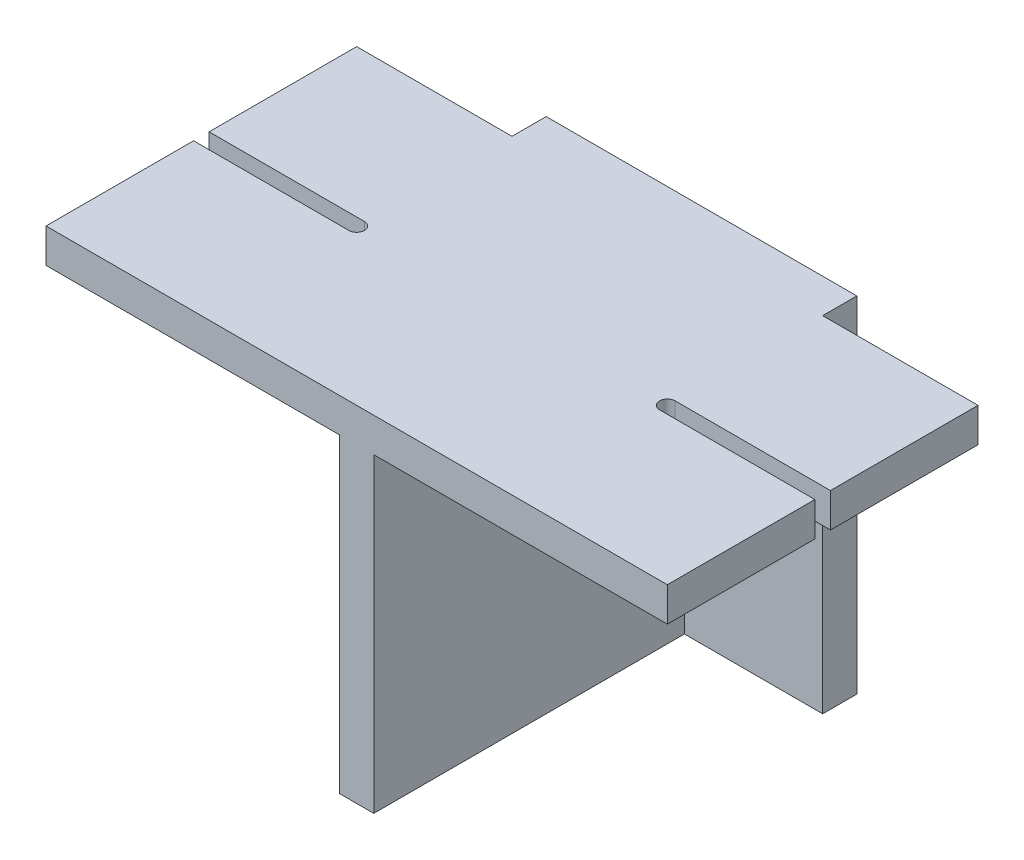
SolidWorks part; units mm, degrees
ref_plane "Plan de face" through (0, 0, 0) normal (0, 0, 1) x (1, 0, 0)
ref_plane "Plan de dessus" through (0, 0, 0) normal (0, 1, 0) x (1, 0, 0)
ref_plane "Plan de droite" through (0, 0, 0) normal (1, 0, 0) x (0, 0, -1)
sketch "Esquisse1" plane through (0, 0, 0) normal (0, 1, 0) x (1, 0, 0)
  line L0 (0, 0) -> (0, -200)
  line L1 (0, -200) -> (-200, -200)
  line L2 (-200, -200) -> (-200, -105)
  line L3 (-200, -105) -> (-100, -105)
  line L5 (-100, -95) -> (-200, -95)
  line L6 (-200, -95) -> (-200, 0)
  line L7 (-200, 0) -> (0, 0)
  arc A0 (-100, -105) -> (-100, -95) centre (-100, -100) ccw
  dimension "D1" = 200
  dimension "D2" = 95
  dimension "D3" = 100
extrude "Boss.-Extru.1" add sketch "Esquisse1" along normal blind 22
mirror "Symétrie1" about plane through (0, 22, 0) normal (-1, 0, 0) of "Boss.-Extru.1"
sketch "Esquisse2" plane through (0, 0, 0) normal (0, -1, 0) x (1, 0, 0)
  line L0 (-11, 0) -> (11, 0)
  line L1 (200, 0) -> (-200, 0) construction
  line L2 (11, 0) -> (11, 200)
  line L3 (-200, 200) -> (200, 200) construction
  line L4 (11, 200) -> (-11, 200)
  line L5 (-11, 200) -> (-11, 0)
  point P6 (0, 0)
  dimension "D1" = 22
extrude "Boss.-Extru.2" add sketch "Esquisse2" along normal blind 200
sketch "Esquisse3" plane through (0, 22, 0) normal (0, 1, 0) x (1, 0, 0)
  line L0 (100, 0) -> (-100, 0)
  line L1 (200, 0) -> (-200, 0) construction
  line L2 (-100, 0) -> (-100, 22)
  line L3 (-100, 22) -> (100, 22)
  line L4 (100, 22) -> (100, 0)
  point P5 (0, 0)
  dimension "D1" = 22
  dimension "D2" = 200
extrude "Boss.-Extru.3" add sketch "Esquisse3" against normal up to surface (222 mm away) up to face at (0, -200, 100)
